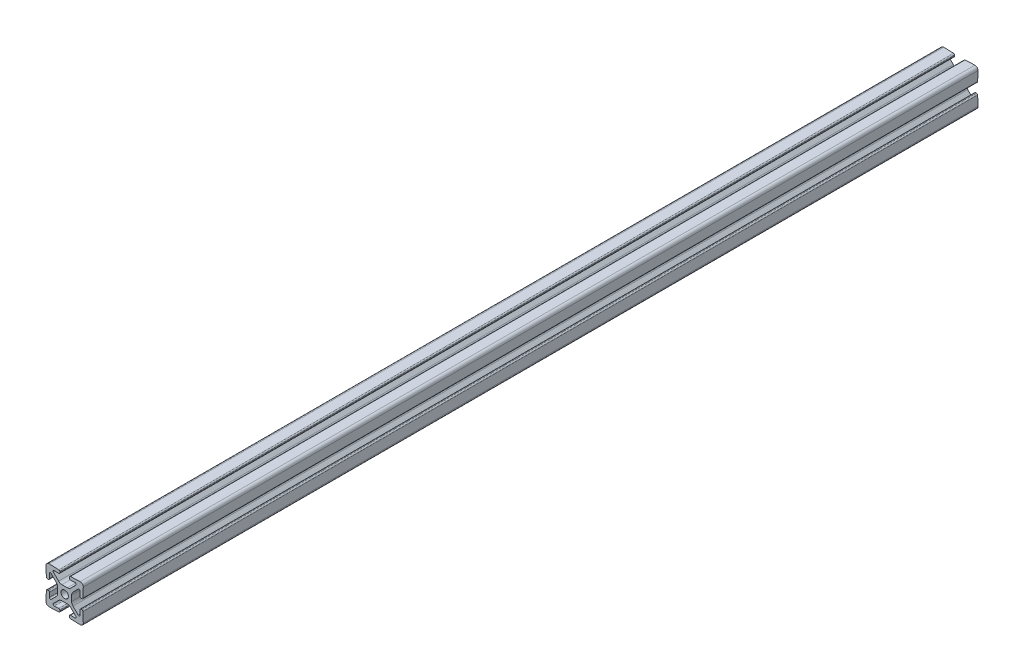
SolidWorks part; units mm, degrees
ref_plane "Front Plane" through (0, 0, 0) normal (0, 0, 1) x (1, 0, 0)
ref_plane "Top Plane" through (0, 0, 0) normal (0, 1, 0) x (1, 0, 0)
ref_plane "Right Plane" through (0, 0, 0) normal (1, 0, 0) x (0, 0, -1)
sketch "Sketch1" plane through (0, 0, 0) normal (0, 0, 1) x (1, 0, 0)
  line L0 (0, 0) -> (0, 12.7) construction
  line L1 (0, 0) -> (12.7, 0) construction
  line L2 (0, 0) -> (-12.7, 12.7) construction
  line L3 (-10.5971, 12.6988) -> (-3.9739, 12.4675)
  line L4 (-12.7, 12.7) -> (0, 12.7) construction
  line L6 (-4.0475, 10.3606) -> (-7.0332, 10.4648)
  line L10 (0, 4.7625) -> (-1.8848, 4.7625)
  line L11 (-4.1299, 5.6924) -> (-7.5996, 9.1622)
  line L24 (0, 0) -> (-12.7, 0) construction
  line L25 (-12.7, 0) -> (0, 0) construction
  line L26 (0, 0) -> (0, -12.7) construction
  line L27 (-12.7, -12.7) -> (-12.7, 12.7) construction
  line L28 (0, 12.7) -> (12.7, 12.7) construction
  line L29 (-3.239, 11.6793) -> (-3.2594, 11.0955)
  line L30 (-12.7, -12.7) -> (12.7, -12.7) construction
  arc A0 (-12.1048, 12.1048) -> (-10.5971, 12.6988) centre (-10.668, 10.668) cw
  arc A6 (-1.8848, 4.7625) -> (-4.1299, 5.6924) centre (-1.8848, 7.9375) cw
  circle A16 centre (0, 0) radius 2.54
  arc A18 (-7.5996, 9.1622) -> (-7.0332, 10.4648) centre (-7.0599, 9.702) cw
  circle A19 centre (-2.3794, 2.3794) radius 0.635 construction
  arc A20 (-4.0475, 10.3606) -> (-3.2594, 11.0955) centre (-4.0209, 11.1221) ccw
  arc A21 (-3.9739, 12.4675) -> (-3.239, 11.6793) centre (-4.0005, 11.7059) cw
  point P15 (0, 0)
  point P42 (-3.1999, 4.7625)
  point P80 (-12.7, 0)
  point P85 (0, -12.7)
  point P88 (0, -12.7)
  dimension "D11" = 2.032
  dimension "D15" = 3.175
  dimension "Center Hole Diameter" = 5.08
  dimension "D6" = 1.27
  dimension "D4" = 0.7633
  dimension "D8" = 0.762
  dimension "D12" = 0.762
  dimension "D1" = 45
  dimension "D2" = 2
  dimension "Rail Width" = 25.4
  dimension "D10" = 2.2098
  dimension "T-Slot Depth" = 7.9375
  dimension "D9" = 2.1082
  dimension "Rail Height" = 25.4
  dimension "D23" = 9.525
  dimension "D5" = 15.6464
  dimension "D3" = 4
  dimension "D7" = 5.7028
  dimension "T-Slot Width" = 6.477
sketch "Sketch2" plane through (0, 0, 0) normal (1, 0, 0) x (0, 0, -1)
  line L0 (-304.8, 0) -> (304.8, 0)
  line L2 (0, 0) -> (0, 12.7) construction
  line L3 (0, 0) -> (0, 12.7) construction
  point P0 (-266.7, 0)
  point P3 (0, 0)
  point P7 (266.7, 0)
  dimension "D1" = 38.1
  dimension "Length" = 609.6
sketch "Sketch3" plane through (0, 0, 0) normal (0, 0, 1) x (1, 0, 0)
  line L2 (0, 4.7625) -> (-1.8848, 4.7625) construction
  line L5 (-4.1299, 5.6924) -> (-7.5996, 9.1622) construction
  line L6 (-4.0475, 10.3606) -> (-7.0332, 10.4648) construction
  line L7 (-3.239, 11.6793) -> (-3.2594, 11.0955) construction
  line L67 (-10.5971, 12.6988) -> (-3.9739, 12.4675) construction
  line L68 (0, 4.7625) -> (-1.8848, 4.7625)
  line L69 (-4.1299, 5.6924) -> (-7.5996, 9.1622)
  line L70 (-4.0475, 10.3606) -> (-7.0332, 10.4648)
  line L71 (-3.239, 11.6793) -> (-3.2594, 11.0955)
  line L72 (-10.5971, 12.6988) -> (-3.9739, 12.4675)
  line L73 (0, 0) -> (-12.7, 12.7) construction
  line L74 (0, 0) -> (-12.7, 12.7) construction
  line L75 (-12.6988, 10.5971) -> (-12.4675, 3.9739)
  line L76 (-11.6793, 3.239) -> (-11.0955, 3.2594)
  line L77 (-10.3606, 4.0475) -> (-10.4648, 7.0332)
  line L78 (-5.6924, 4.1299) -> (-9.1622, 7.5996)
  line L79 (-4.7625, 0) -> (-4.7625, 1.8848)
  line L80 (-4.7625, 0) -> (-2.54, 0)
  line L82 (0, 4.7625) -> (0, 2.54)
  arc A3 (-4.1299, 5.6924) -> (-1.8848, 4.7625) centre (-1.8848, 7.9375) ccw construction
  circle A10 centre (0, 0) radius 2.54
  arc A56 (0, 2.54) -> (-2.54, 0) centre (0, 0) ccw
  arc A57 (-7.0332, 10.4648) -> (-7.5996, 9.1622) centre (-7.0599, 9.702) ccw construction
  arc A58 (-4.0475, 10.3606) -> (-3.2594, 11.0955) centre (-4.0209, 11.1221) ccw construction
  arc A59 (-3.239, 11.6793) -> (-3.9739, 12.4675) centre (-4.0005, 11.7059) ccw construction
  arc A60 (-10.5971, 12.6988) -> (-12.1048, 12.1048) centre (-10.668, 10.668) ccw construction
  arc A61 (-4.1299, 5.6924) -> (-1.8848, 4.7625) centre (-1.8848, 7.9375) ccw
  arc A62 (-7.0332, 10.4648) -> (-7.5996, 9.1622) centre (-7.0599, 9.702) ccw
  arc A63 (-4.0475, 10.3606) -> (-3.2594, 11.0955) centre (-4.0209, 11.1221) ccw
  arc A64 (-3.239, 11.6793) -> (-3.9739, 12.4675) centre (-4.0005, 11.7059) ccw
  arc A65 (-10.5971, 12.6988) -> (-12.6988, 10.5971) centre (-10.668, 10.668) ccw
  arc A67 (-11.6793, 3.239) -> (-12.4675, 3.9739) centre (-11.7059, 4.0005) cw
  arc A68 (-10.3606, 4.0475) -> (-11.0955, 3.2594) centre (-11.1221, 4.0209) cw
  arc A69 (-10.4648, 7.0332) -> (-9.1622, 7.5996) centre (-9.702, 7.0599) cw
  arc A70 (-5.6924, 4.1299) -> (-4.7625, 1.8848) centre (-7.9375, 1.8848) cw
  dimension "D1" = 0
extrude "Boss-Extrude1" add sketch "Sketch3" along normal mid plane 609.6
pattern_circular "CirPattern1" count 4 over 360 about axis through (0, 0, 0) along (0, 0, 1) of "Boss-Extrude1"
ref_plane "Contact Plane 1" through (0, 12.7, 0) normal (0, 1, 0) x (1, 0, 0)
ref_plane "Contact Plane 2" through (12.7, 0, 0) normal (1, 0, 0) x (0, 0, -1)
ref_plane "Contact Plane 3" through (0, -12.7, 0) normal (0, -1, 0) x (-1, 0, 0)
ref_plane "Contact Plane 4" through (-12.7, 0, 0) normal (-1, 0, 0) x (0, 0, 1)
equation "\"D1@Sketch2\"=\"Rail Width@Sketch1\"*1.5"
equation "\"D1@Boss-Extrude1\"=\"Length@Sketch2\""
